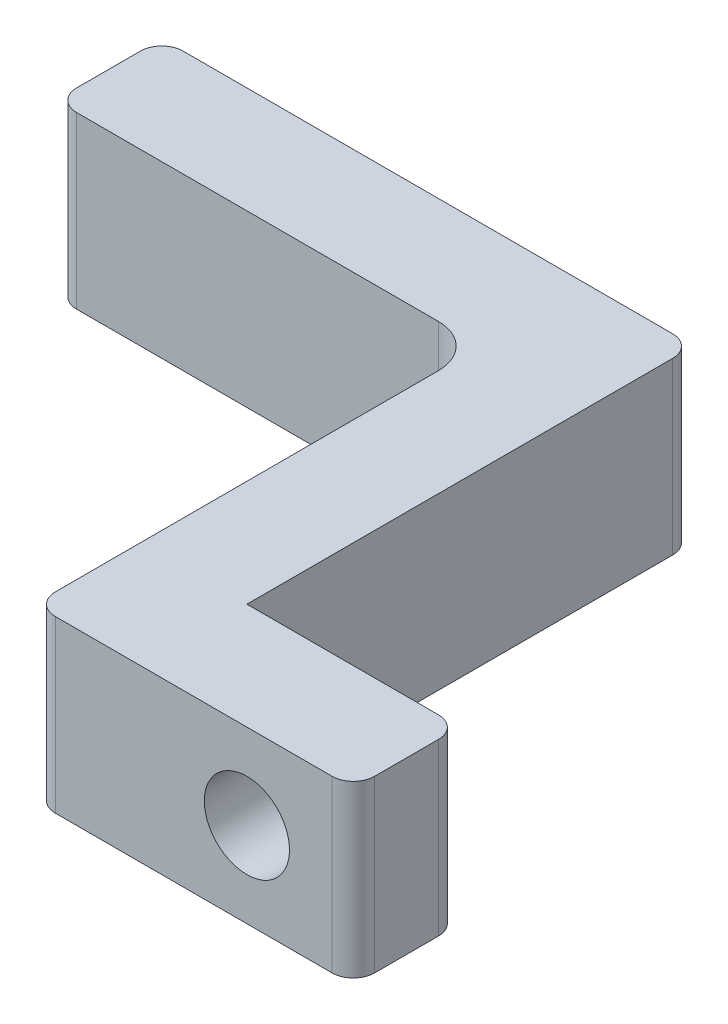
SolidWorks part; units mm, degrees
ref_plane "前视基准面" through (0, 0, 0) normal (0, 0, 1) x (1, 0, 0)
ref_plane "上视基准面" through (0, 0, 0) normal (0, 1, 0) x (1, 0, 0)
ref_plane "右视基准面" through (0, 0, 0) normal (1, 0, 0) x (0, 0, -1)
other "Configuration Table"
sketch "草图1" plane through (0, 0, 0) normal (0, 1, 0) x (1, 0, 0)
  line L0 (-2, 0) -> (-20, 0)
  line L2 (0, -2) -> (0, -21)
  line L3 (0, -21) -> (5, -21)
  line L4 (5, 0) -> (5, -16)
  line L5 (0, -21) -> (15, -21)
  line L6 (0, -21) -> (0, -15.7202)
  line L7 (5, -16) -> (15, -16)
  line L8 (15, -21) -> (15, -16)
  line L10 (5, 0) -> (5, 5)
  line L11 (5, 5) -> (-20, 5)
  line L12 (-20, 0) -> (-20, 5)
  arc A0 (-2, 0) -> (0, -2) centre (-2, -2) cw
  point P5 (0, 0)
  dimension "D6" = 2
  dimension "D1" = 2
  dimension "D2" = 5
  dimension "D3" = 10
  dimension "D4" = 25
  dimension "D5" = 5
  dimension "D7" = 5
extrude "凸台-拉伸1" add sketch "草图1" along normal blind 8 contours L0 A0 L2 L3 L5 L8 L7 L4 L10 L11 L12
sketch "草图2" plane through (0, 0, 16) normal (0, 0, -1) x (-1, 0, 0)
  line L0 (-10, 8) -> (-10, 0) construction
  line L1 (-5, 8) -> (-15, 8) construction
  line L2 (-5, 0) -> (-15, 0) construction
  line L3 (-15, 4) -> (-5, 4) construction
  line L4 (-15, 8) -> (-15, 0) construction
  line L5 (-5, 8) -> (-5, 0) construction
  circle A0 centre (-10, 4) radius 2
  point P14 (0, 0)
  point P15 (-10, 4)
  dimension "D1" = 4
extrude "切除-拉伸1" cut sketch "草图2" against normal blind 5
fillet "圆角1" radius 1 6 edges at (-20, 4, -5) (-20, 4, 0) (0, 4, 21) (15, 4, 21) (15, 4, 16) (5, 4, -5)
